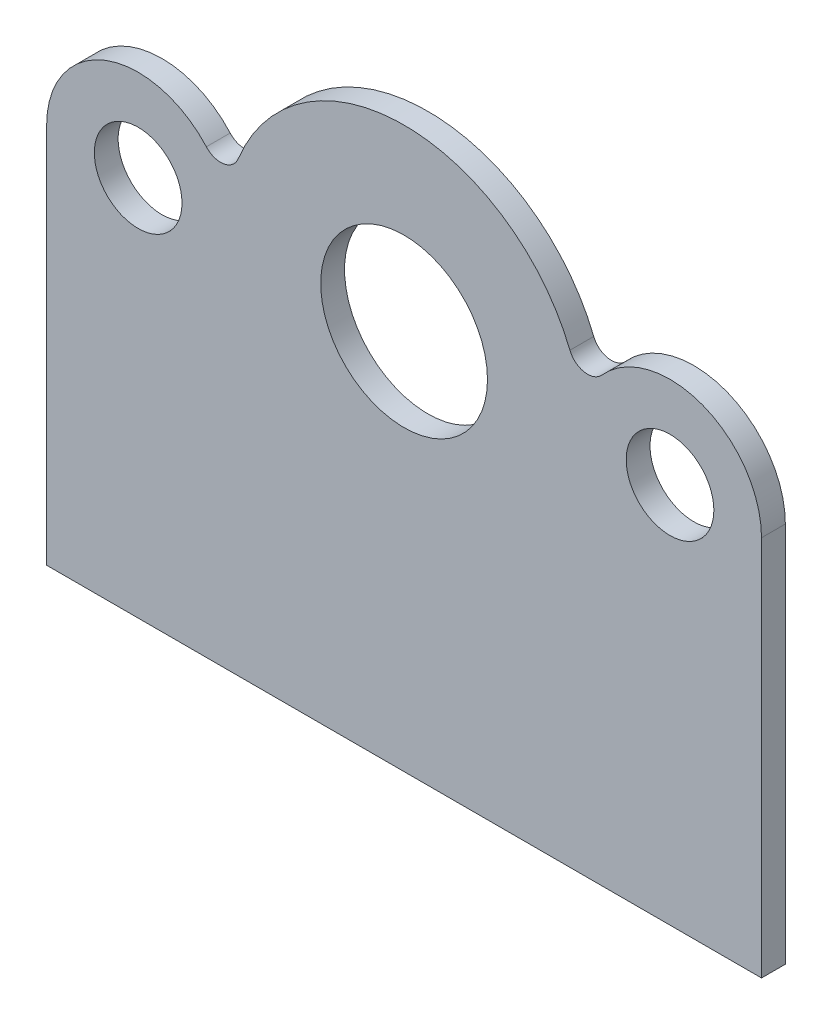
SolidWorks part; units mm, degrees
material "AISI 4130 Steel, annealed at 865C"
ref_plane "X-Y Datum" through (0, 0, 0) normal (0, 0, 1) x (1, 0, 0)
ref_plane "X-Z Datum" through (0, 0, 0) normal (0, 1, 0) x (1, 0, 0)
ref_plane "Y-Z Datum" through (0, 0, 0) normal (1, 0, 0) x (0, 0, -1)
sketch "Sketch1" plane through (0, 0, 0) normal (0, 0, 1) x (1, 0, 0)
  line L0 (23.8125, 0) -> (23.8125, 25.4) construction
  line L1 (0, 0) -> (47.625, 0)
  line L2 (0, 0) -> (0, 25.4)
  line L4 (47.625, 0) -> (47.625, 25.4)
  line L7 (0, 25.4) -> (23.8125, 25.4) construction
  line L8 (23.8125, 25.4) -> (47.625, 25.4) construction
  circle A1 centre (23.8125, 25.4) radius 5.5562
  circle A2 centre (6.096, 25.4) radius 2.921
  circle A3 centre (41.529, 25.4) radius 2.921
  arc A5 (10.6393, 29.4645) -> (0, 25.4) centre (6.096, 25.4) ccw
  arc A6 (47.625, 25.4) -> (36.9857, 29.4645) centre (41.529, 25.4) ccw
  arc A7 (34.8608, 29.8379) -> (12.7642, 29.8379) centre (23.8125, 25.4) ccw
  circle A8 centre (6.096, 25.4) radius 6.096 construction
  arc A9 (34.8608, 29.8379) -> (36.9857, 29.4645) centre (36.0392, 30.3113) ccw
  circle A10 centre (41.529, 25.4) radius 6.096 construction
  arc A11 (10.6393, 29.4645) -> (12.7642, 29.8379) centre (11.5858, 30.3113) ccw
  point P20 (35.1985, 28.8811)
  point P23 (11.9256, 27.1823)
  point P27 (47.3586, 27.1823)
  dimension "D4" = 5.842
  dimension "D5" = 11.1125
  dimension "D6" = 5.842
  dimension "D8" = 1.27
  dimension "D1" = 47.625
  dimension "D2" = 25.4
  dimension "D7" = 6.35
  dimension "D3" = 3.175
extrude "Boss-Extrude1" add sketch "Sketch1" along normal blind 1.5875
equation "\"Fastener Diameter\"= 7 / 16in"
equation "\"Spring Diameter\"= .23in"
equation "\"D6@Sketch1\"=\"Spring Diameter\""
equation "\"D4@Sketch1\"=\"Spring Diameter\""
equation "\"D5@Sketch1\"=\"Fastener Diameter\""
